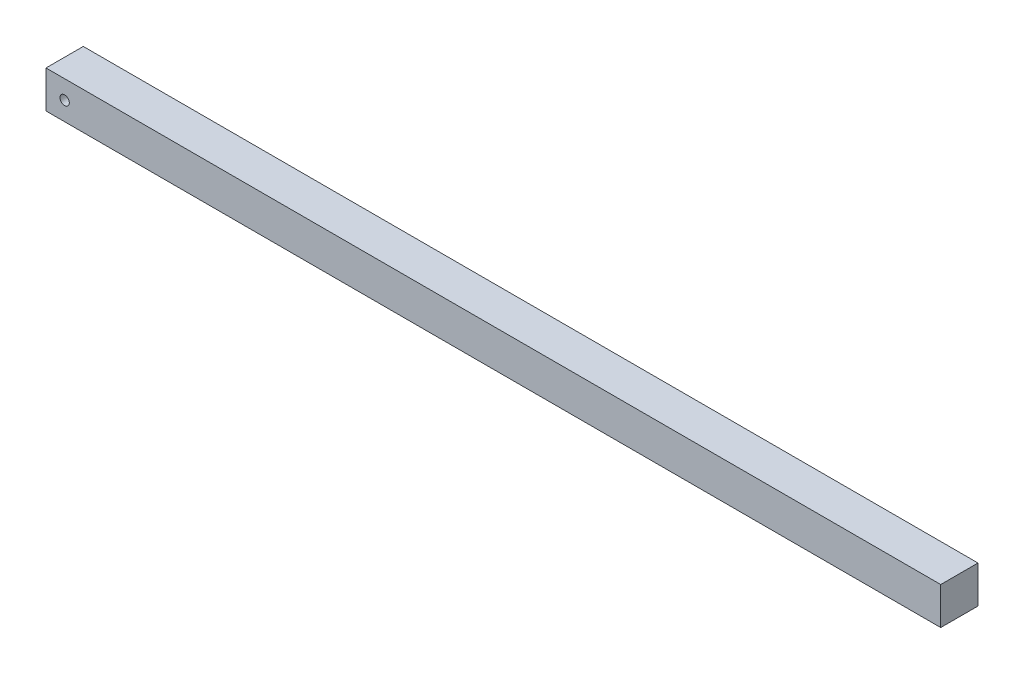
SolidWorks part; units mm, degrees
ref_plane "Front Plane" through (0, 0, 0) normal (0, 0, 1) x (1, 0, 0)
ref_plane "Top Plane" through (0, 0, 0) normal (0, 1, 0) x (1, 0, 0)
ref_plane "Right Plane" through (0, 0, 0) normal (1, 0, 0) x (0, 0, -1)
sketch "Sketch1" plane through (0, 0, 0) normal (1, 0, 0) x (0, 0, -1)
  line L1 (0, 0) -> (25.4, 0)
  line L2 (0, 0) -> (0, -25.4)
  line L3 (0, -25.4) -> (25.4, -25.4)
  line L4 (25.4, 0) -> (25.4, -25.4)
  dimension "D1" = 25.4
  dimension "D2" = 25.4
extrude "Boss-Extrude1" add sketch "Sketch1" along normal blind 609.6
sketch "Sketch5" plane through (0, 0, 0) normal (0, 0, 1) x (1, 0, 0)
  line L0 (609.6, 0) -> (0, 0) construction
  line L1 (0, 0) -> (0, -25.4) construction
  circle A0 centre (12.7, -12.7) radius 3.175
  point P4 (0, 0)
  point P6 (10.3833, -13.6944)
  dimension "D3" = 6.35
  dimension "D1" = 12.7
  dimension "D2" = 12.7
extrude "Cut-Extrude1" cut sketch "Sketch5" against normal through all
